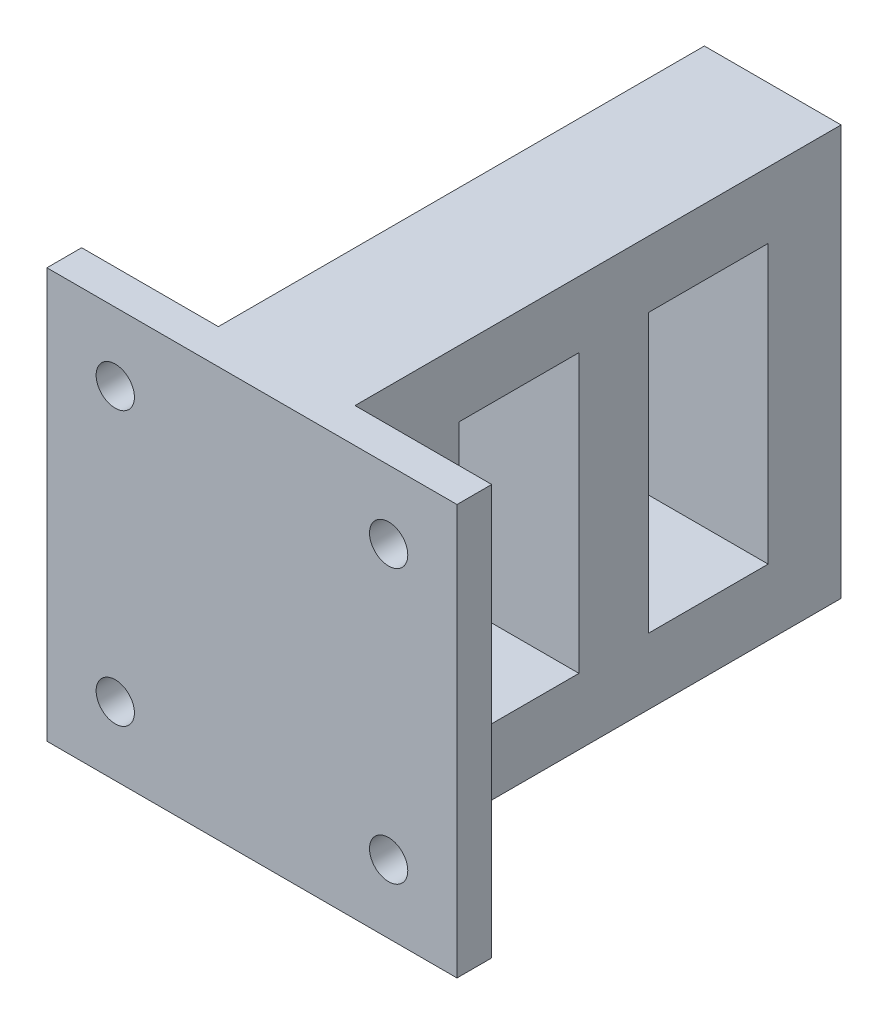
SolidWorks part; units mm, degrees
ref_plane "Front Plane" through (0, 0, 0) normal (0, 0, 1) x (1, 0, 0)
ref_plane "Top Plane" through (0, 0, 0) normal (0, 1, 0) x (1, 0, 0)
ref_plane "Right Plane" through (0, 0, 0) normal (1, 0, 0) x (0, 0, -1)
sketch "Sketch2" plane through (0, 0, 0) normal (0, 0, 1) x (1, 0, 0)
  line L0 (15, 0) -> (15, 30) construction
  line L1 (0, 0) -> (30, 0)
  line L2 (0, 0) -> (0, 30)
  line L3 (0, 30) -> (30, 30)
  line L4 (30, 0) -> (30, 30)
  circle A0 centre (5, 5) radius 1.4
  circle A1 centre (25, 5) radius 1.4
  circle A2 centre (5, 25) radius 1.4
  circle A3 centre (25, 25) radius 1.4
  dimension "D3" = 5
  dimension "D4" = 5
  dimension "D5" = 5
  dimension "D6" = 5
  dimension "D7" = 5
  dimension "D8" = 5
  dimension "D9" = 5
  dimension "D10" = 5
  dimension "D1" = 30
  dimension "D2" = 30
extrude "Boss-Extrude1" add sketch "Sketch2" along normal blind 2.54
sketch "Sketch3" plane through (0, 0, 0) normal (0, 0, -1) x (-1, 0, 0)
  line L0 (-15, 0) -> (-15, 30) construction
  line L1 (0, 0) -> (-30, 0) construction
  line L2 (-30, 30) -> (0, 30) construction
  line L4 (-10, 0) -> (-20, 0)
  line L5 (-10, 0) -> (-10, 30)
  line L6 (-10, 30) -> (-20, 30)
  line L7 (-20, 0) -> (-20, 30)
  dimension "D1" = 10
  dimension "D2" = 5
extrude "Boss-Extrude2" add sketch "Sketch3" along normal blind 35.56
sketch "Sketch4" plane through (10, 0, 0) normal (-1, 0, 0) x (0, 0, 1)
  line L0 (-35.56, 0) -> (0, 0) construction
  line L1 (-30.226, 4.84) -> (-21.463, 4.84)
  line L2 (-30.226, 4.84) -> (-30.226, 25.16)
  line L3 (-30.226, 25.16) -> (-21.463, 25.16)
  line L4 (-21.463, 4.84) -> (-21.463, 25.16)
  line L5 (-16.383, 4.84) -> (-7.62, 4.84)
  line L6 (-16.383, 4.84) -> (-16.383, 25.16)
  line L7 (-16.383, 25.16) -> (-7.62, 25.16)
  line L8 (-7.62, 4.84) -> (-7.62, 25.16)
  line L9 (0, 0) -> (0, 30) construction
  dimension "D1" = 20.32
  dimension "D2" = 20.32
  dimension "D3" = 4.84
  dimension "D4" = 4.84
  dimension "D5" = 8.763
  dimension "D6" = 8.763
  dimension "D7" = 7.62
  dimension "D8" = 5.08
extrude "Cut-Extrude1" cut sketch "Sketch4" against normal blind 35.56
